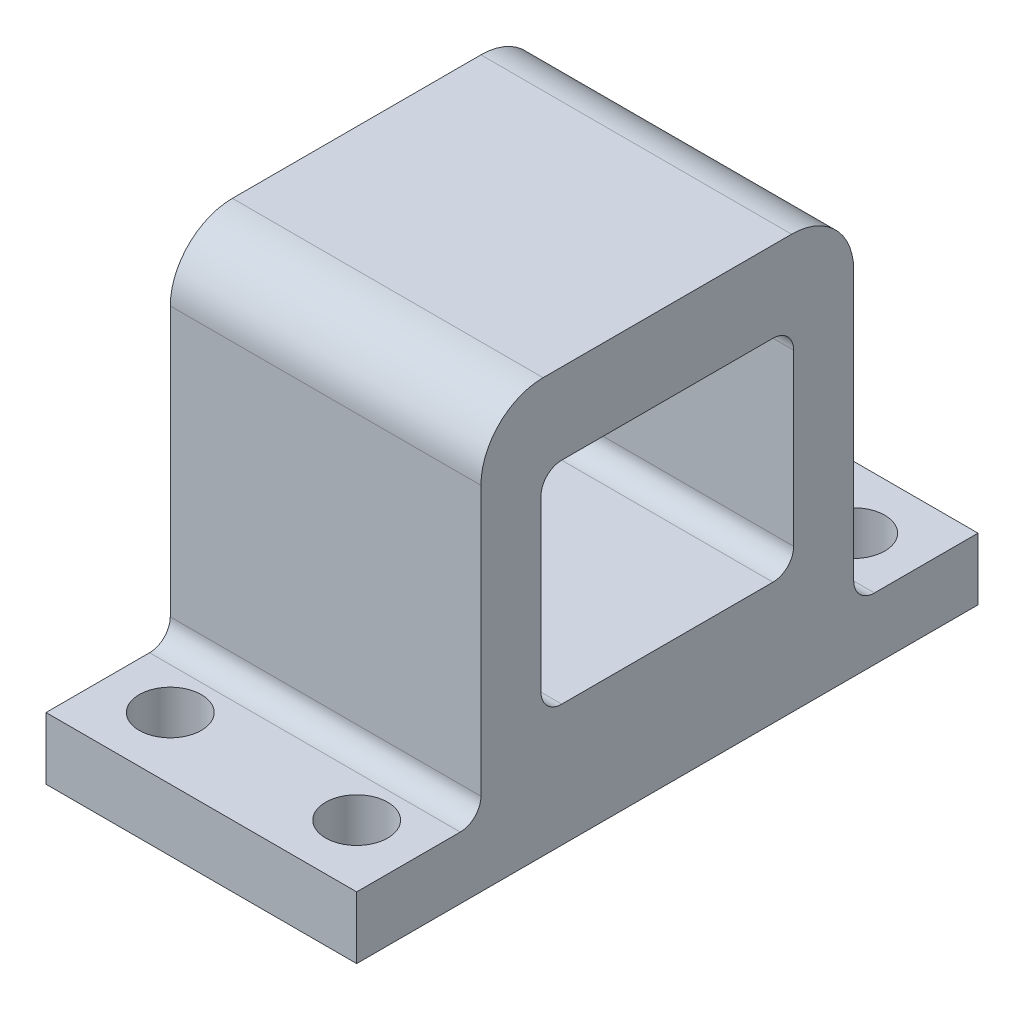
SolidWorks part; units mm, degrees
ref_plane "Front Plane" through (0, 0, 0) normal (0, 0, 1) x (1, 0, 0)
ref_plane "Top Plane" through (0, 0, 0) normal (0, 1, 0) x (1, 0, 0)
ref_plane "Right Plane" through (0, 0, 0) normal (1, 0, 0) x (0, 0, -1)
sketch "Sketch1" plane through (0, 0, 0) normal (0, 1, 0) x (1, 0, 0)
  line L1 (0, 0) -> (-15, 0)
  line L2 (0, 0) -> (0, 30)
  line L3 (0, 30) -> (-15, 30)
  line L4 (-15, 0) -> (-15, 30)
  dimension "D1" = 30
  dimension "D2" = 15
extrude "Boss-Extrude2" add sketch "Sketch1" along normal blind 3
sketch "Sketch3" plane through (0, 3, 0) normal (0, 1, 0) x (1, 0, 0)
  line L0 (-15, 30) -> (-15, 0) construction
  line L1 (-15, 15) -> (0, 15)
  line L2 (-15, 15) -> (-15, 6)
  line L3 (-15, 6) -> (0, 6)
  line L4 (0, 15) -> (0, 6)
  line L5 (0, 0) -> (0, 30) construction
  line L6 (-15, 0) -> (0, 0) construction
  line L7 (-15, 15) -> (0, 15)
  line L8 (-15, 15) -> (-15, 24)
  line L9 (-15, 24) -> (0, 24)
  line L10 (0, 15) -> (0, 24)
  line L11 (0, 30) -> (-15, 30) construction
  circle A0 centre (-12, 27) radius 1.5
  circle A1 centre (-3, 27) radius 1.5
  circle A2 centre (-12, 3) radius 1.5
  circle A3 centre (-3, 3) radius 1.5
  point P13 (0, 0)
  point P20 (0, 0)
  dimension "D5" = 3
  dimension "D6" = 3
  dimension "D9" = 3
  dimension "D12" = 3
  dimension "D1" = 9
  dimension "D2" = 9
  dimension "D3" = 3
  dimension "D4" = 3
  dimension "D7" = 3
  dimension "D8" = 3
  dimension "D10" = 3
  dimension "D11" = 3
  dimension "D13" = 3
  dimension "D14" = 3
extrude "Cut-Extrude1" cut sketch "Sketch3" against normal blind 3 contours A0 | A1 | A3 | A2
sketch "Sketch5" plane through (0, 3, 0) normal (0, 1, 0) x (1, 0, 0)
  line L0 (-15, 30) -> (-15, 0) construction
  line L1 (-15, 15) -> (0, 15)
  line L2 (-15, 15) -> (-15, 24)
  line L3 (-15, 24) -> (0, 24)
  line L4 (0, 15) -> (0, 24)
  line L5 (0, 0) -> (0, 30) construction
  line L7 (-15, 15) -> (0, 15)
  line L8 (-15, 15) -> (-15, 6)
  line L9 (-15, 6) -> (0, 6)
  line L10 (0, 15) -> (0, 6)
  line M8 (0, 0) -> (0, 30)
  line M10 (-15, 30) -> (-15, 0)
  dimension "D1" = 9
  dimension "D2" = 9
extrude "Boss-Extrude3" add sketch "Sketch5" along normal blind 17 contours L3 L1 M10 M8 | L9 L1 M10 M8
fillet "Fillet1" radius 1 1 edges at (-7.5, 3, -6)
fillet "Fillet2" radius 1 1 edges at (-7.5, 3, -24)
sketch "Sketch6" plane through (0, 0, 0) normal (1, 0, 0) x (0, 0, -1)
  line L0 (0, 0) -> (30, 0) construction
  line L1 (8.9, 16.1) -> (21.1, 16.1)
  line L2 (8.9, 16.1) -> (8.9, 5.9)
  line L3 (8.9, 5.9) -> (21.1, 5.9)
  line L4 (21.1, 16.1) -> (21.1, 5.9)
  line L5 (24, 20) -> (24, 4) construction
  line L7 (6, 20) -> (6, 4) construction
  dimension "D1" = 10.2
  dimension "D2" = 12.2
  dimension "D3" = 5.9
  dimension "D4" = 2.9
  dimension "D5" = 2.9
extrude "Cut-Extrude2" cut sketch "Sketch6" against normal through all contours L2 L1 L4 L3
fillet "Fillet3" radius 3 1 edges at (-7.5, 20, -24)
fillet "Fillet4" radius 3 1 edges at (-7.5, 20, -6)
fillet "Fillet5" radius 1 1 edges at (-7.5, 5.9, -8.9)
fillet "Fillet6" radius 1 1 edges at (-7.5, 16.1, -8.9)
fillet "Fillet7" radius 1 1 edges at (-7.5, 16.1, -21.1)
fillet "Fillet8" radius 1 1 edges at (-7.5, 5.9, -21.1)
